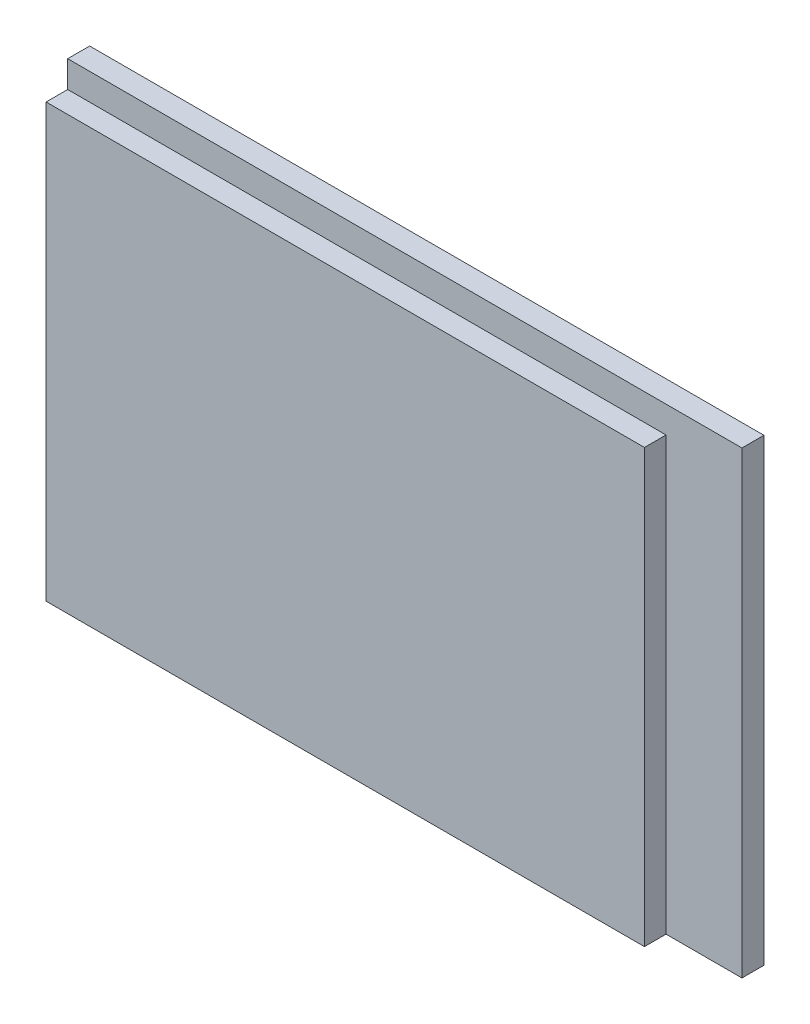
SolidWorks part; units mm, degrees
material "ABS PC"
ref_plane "Front Plane" through (0, 0, 0) normal (0, 0, 1) x (1, 0, 0)
ref_plane "Top Plane" through (0, 0, 0) normal (0, 1, 0) x (1, 0, 0)
ref_plane "Right Plane" through (0, 0, 0) normal (1, 0, 0) x (0, 0, -1)
sketch "Sketch1" plane through (0, 0, 0) normal (0, 0, 1) x (1, 0, 0)
  line L1 (-38.989, -26.543) -> (38.989, -26.543)
  line L2 (-38.989, -26.543) -> (-38.989, 26.543)
  line L3 (-38.989, 26.543) -> (38.989, 26.543)
  line L4 (38.989, -26.543) -> (38.989, 26.543)
  line L5 (-38.989, -26.543) -> (38.989, 26.543) construction
  line L6 (-38.989, 26.543) -> (38.989, -26.543) construction
  point P0 (0, 0)
  dimension "D1" = 53.086
  dimension "D2" = 77.978
extrude "Boss-Extrude1" add sketch "Sketch1" along normal blind 2.54
sketch "Sketch2" plane through (0, 0, 2.54) normal (0, 0, 1) x (1, 0, 0)
  line L1 (-38.989, -26.543) -> (30.211, -26.543)
  line L2 (-38.989, -26.543) -> (-38.989, 23.457)
  line L3 (-38.989, 23.457) -> (30.211, 23.457)
  line L4 (30.211, -26.543) -> (30.211, 23.457)
  dimension "D1" = 50
  dimension "D2" = 69.2
extrude "Boss-Extrude2" add sketch "Sketch2" along normal blind 2.5
